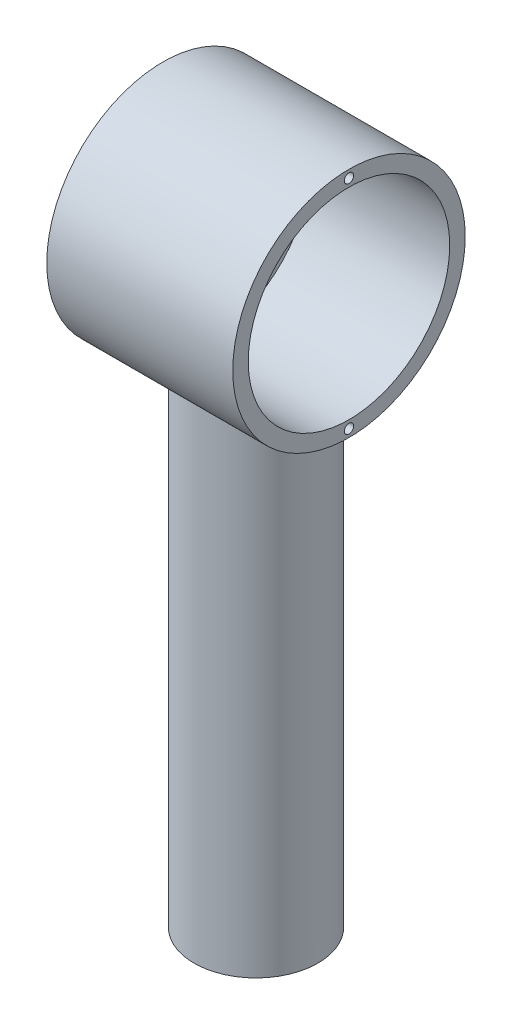
SolidWorks part; units mm, degrees
material "1060 Alloy"
ref_plane "Front Plane" through (0, 0, 0) normal (0, 0, 1) x (1, 0, 0)
ref_plane "Top Plane" through (0, 0, 0) normal (0, 1, 0) x (1, 0, 0)
ref_plane "Right Plane" through (0, 0, 0) normal (1, 0, 0) x (0, 0, -1)
sketch "Sketch1" plane through (0, 0, 0) normal (0, 1, 0) x (1, 0, 0)
  line L3 (14.4338, 0) -> (7.2169, 12.5)
  line L4 (7.2169, 12.5) -> (-7.2169, 12.5)
  line L5 (-7.2169, 12.5) -> (-14.4338, 0)
  line L6 (-14.4338, 0) -> (-7.2169, -12.5)
  line L7 (-7.2169, -12.5) -> (7.2169, -12.5)
  line L8 (7.2169, -12.5) -> (14.4338, 0)
  circle A0 centre (0, 0) radius 20
  circle A1 centre (0, 0) radius 12.5 construction
  dimension "D1" = 40
extrude "Boss-Extrude1" add sketch "Sketch1" along normal blind 25
sketch "Sketch2" plane through (0, 0, 0) normal (0, -1, 0) x (1, 0, 0)
  circle A1 centre (0, 0) radius 20
extrude "Boss-Extrude2" add sketch "Sketch2" along normal blind 100
ref_plane "Plane1" through (20, 0, 0) normal (1, 0, 0) x (0, 0, -1)
sketch "Sketch5" plane through (0, 0, 0) normal (0, 1, 0) x (1, 0, 0)
  line L1 (14.4338, 0) -> (7.2169, 12.5)
  line L2 (7.2169, 12.5) -> (-7.2169, 12.5)
  line L3 (-7.2169, 12.5) -> (-14.4338, 0)
  line L4 (-14.4338, 0) -> (-7.2169, -12.5)
  line L5 (-7.2169, -12.5) -> (7.2169, -12.5)
  line L6 (7.2169, -12.5) -> (14.4338, 0)
  circle A0 centre (0, 0) radius 12.5 construction
sketch "Sketch6" plane through (0, 25, 0) normal (0, 1, 0) x (1, 0, 0)
  circle A0 centre (0, 0) radius 20
  dimension "D1" = 40
extrude "Boss-Extrude4" add sketch "Sketch6" against normal blind 100
sketch "Sketch7" plane through (20, 0, 0) normal (1, 0, 0) x (0, 0, -1)
  circle A2 centre (0, 39.2866) radius 25
  dimension "D3" = 50
extrude "Cut-Extrude2" cut sketch "Sketch7" against normal blind 40
sketch "Sketch8" plane through (20, 0, 0) normal (1, 0, 0) x (0, 0, -1)
  circle A0 centre (0, 39.2528) radius 25
  circle A1 centre (0, 39.2528) radius 22.5
  dimension "D1" = 50
  dimension "D2" = 45
extrude "Boss-Extrude7" add sketch "Sketch8" against normal blind 40 contours A1 | A0
sketch "Sketch9" plane through (20, 0, 0) normal (1, 0, 0) x (0, 0, -1)
  circle A0 centre (0, 39.2528) radius 25
extrude "Boss-Extrude8" add sketch "Sketch9" against normal blind 2
sketch "Sketch10" plane through (18, 0, 0) normal (-1, 0, 0) x (0, 0, 1)
  line L1 (-15.0811, 22.5552) -> (15.0811, 22.5552)
  arc A1 (-15.0811, 22.5552) -> (15.0811, 22.5552) centre (0, 39.2528) ccw
extrude "Boss-Extrude10" add sketch "Sketch10" along normal blind 38
sketch "Sketch11" plane through (0, -100, 0) normal (0, -1, 0) x (1, 0, 0)
  line L0 (0, 20) -> (0, 0)
  line L1 (0, 0) -> (20, 0)
  line L2 (20, -27.5) -> (20, 27.5) construction
  line L4 (0, 14.4338) -> (-12.5, 7.2169)
  line L5 (-12.5, 7.2169) -> (-12.5, -7.2169)
  line L6 (-12.5, -7.2169) -> (0, -14.4338)
  line L7 (0, -14.4338) -> (12.5, -7.2169)
  line L8 (12.5, -7.2169) -> (12.5, 7.2169)
  line L9 (12.5, 7.2169) -> (0, 14.4338)
  arc A0 (20, 0) -> (-20, 0) centre (0, 0) ccw construction
  circle A1 centre (0, 0) radius 12.5 construction
extrude "Cut-Extrude3" cut sketch "Sketch11" against normal blind 25 contours L8 L9 L0 L1 | L7 L8 L1 L0 L4 L5 L6
sketch "Sketch12" plane through (20, 0, 0) normal (1, 0, 0) x (0, 0, -1)
  circle A0 centre (0, 39.2528) radius 25
extrude "Cut-Extrude4" cut sketch "Sketch12" against normal blind 75
sketch "Sketch13" plane through (20, 0, 0) normal (1, 0, 0) x (0, 0, -1)
  circle A0 centre (0, 39.3347) radius 37.5
  dimension "D1" = 75
sketch "Sketch14" plane through (0, -100, 0) normal (0, -1, 0) x (1, 0, 0)
  line L1 (0, -14.4338) -> (12.5, -7.2169)
  line L2 (12.5, -7.2169) -> (12.5, 7.2169)
  line L3 (12.5, 7.2169) -> (0, 14.4338)
  line L4 (0, 14.4338) -> (-12.5, 7.2169)
  line L5 (-12.5, 7.2169) -> (-12.5, -7.2169)
  line L6 (-12.5, -7.2169) -> (0, -14.4338)
  circle A0 centre (0, 0) radius 12.5 construction
  circle A1 centre (0, 0) radius 20
extrude "Boss-Extrude11" add sketch "Sketch14" along normal blind 50
extrude "Boss-Extrude12" add sketch "Sketch13" against normal blind 50 and the other way blind 10
sketch "Sketch16" plane through (30, 0, 0) normal (1, 0, 0) x (0, 0, -1)
  line L0 (-17.3205, 17.3347) -> (17.3205, 17.3347)
  line L1 (0, 67.3347) -> (24.1903, 67.3347)
  circle A0 centre (0, 39.3347) radius 28
  dimension "D1" = 56
  dimension "D2" = 50
sketch "Sketch17" plane through (30, 0, 0) normal (1, 0, 0) x (0, 0, -1)
  circle A0 centre (0, 39.3347) radius 32.5
  dimension "D1" = 65
extrude "Cut-Extrude5" cut sketch "Sketch17" against normal blind 50 contours A0
sketch "Sketch18" plane through (30, 0, 0) normal (1, 0, 0) x (0, 0, -1)
  circle A0 centre (0, 39.3347) radius 32.5
  circle A1 centre (0, 39.3347) radius 37.5
extrude "Boss-Extrude13" add sketch "Sketch18" along normal blind 2
sketch "Sketch19" plane through (32, 0, 0) normal (1, 0, 0) x (0, 0, -1)
  line L0 (0, 71.8347) -> (0, 76.8347)
  line L1 (0, 76.8347) -> (0, 74.3347)
  line L2 (0, 74.3347) -> (3.9271, 74.3347)
  line L3 (0, 6.8347) -> (0, 1.8347)
  line L4 (0, 1.8347) -> (0, 4.3347)
  line L5 (0, 4.3347) -> (3.9271, 4.3347)
  circle A0 centre (0, 39.3347) radius 32.5 construction
  circle A1 centre (0, 39.3347) radius 32.5 construction
  circle A2 centre (0, 39.3347) radius 37.5 construction
  arc A3 (-20, 7.6133) -> (20, 7.6133) centre (0, 39.3347) ccw construction
sketch "Sketch21" plane through (32, 0, 0) normal (1, 0, 0) x (0, 0, -1)
  circle A0 centre (0, 39.3347) radius 32.5
  circle A1 centre (0, 39.3347) radius 37.5
extrude "Cut-Extrude6" cut sketch "Sketch21" against normal blind 2
sketch "Sketch22" plane through (30, 0, 0) normal (1, 0, 0) x (0, 0, -1)
  circle A0 centre (0, 74.3347) radius 1.5
  circle A1 centre (0, 4.3347) radius 1.5
  dimension "D1" = 3
  dimension "D2" = 3
extrude "Cut-Extrude7" cut sketch "Sketch22" against normal blind 10
sketch "Sketch23" plane through (-20, 0, 0) normal (1, 0, 0) x (0, 0, -1)
  line L0 (0, 71.8347) -> (0, 66.8347)
  dimension "D1" = 5
sketch "Sketch26" plane through (-20, 0, 0) normal (1, 0, 0) x (0, 0, -1)
  circle A0 centre (0, 66.8347) radius 0.4
  dimension "D1" = 0.8
sketch "Sketch27" plane through (-20, 0, 0) normal (1, 0, 0) x (0, 0, -1)
  circle A0 centre (0, 39.3347) radius 32.5
  dimension "D1" = 65
extrude "Boss-Extrude14" add sketch "Sketch27" along normal blind 5
sketch "Sketch28" plane through (-15, 0, 0) normal (1, 0, 0) x (0, 0, -1)
  line L0 (0, 67.3347) -> (0, 48.7084)
  line L1 (-15.2706, 64.4693) -> (23.7896, 64.4693)
  line L2 (-0.1626, 66.4693) -> (-15.6668, 66.4693)
  line L3 (-15.6668, 66.4693) -> (19.3425, 66.4693)
  circle A1 centre (0, 66.8347) radius 0.4 construction
  circle A3 centre (-7.975, 64.4693) radius 1
  circle A4 centre (7.975, 64.4693) radius 1
  dimension "D1" = 2
  dimension "D2" = 2
  dimension "D3" = 7.975
  dimension "D4" = 7.975
  dimension "D5" = 2
extrude "Cut-Extrude8" cut sketch "Sketch28" against normal blind 5 contours L1 A3 | L1 A3 | L1 A4 | L1 A4
sketch "Sketch29" plane through (-20, 0, 0) normal (1, 0, 0) x (0, 0, -1)
  circle A0 centre (7.975, 64.4693) radius 1
extrude "Cut-Extrude9" cut sketch "Sketch29" against normal blind 2.5
sketch "Sketch30" plane through (-20, 0, 0) normal (1, 0, 0) x (0, 0, -1)
  circle A0 centre (-7.975, 64.4693) radius 1
extrude "Cut-Extrude10" cut sketch "Sketch30" against normal blind 2.5
